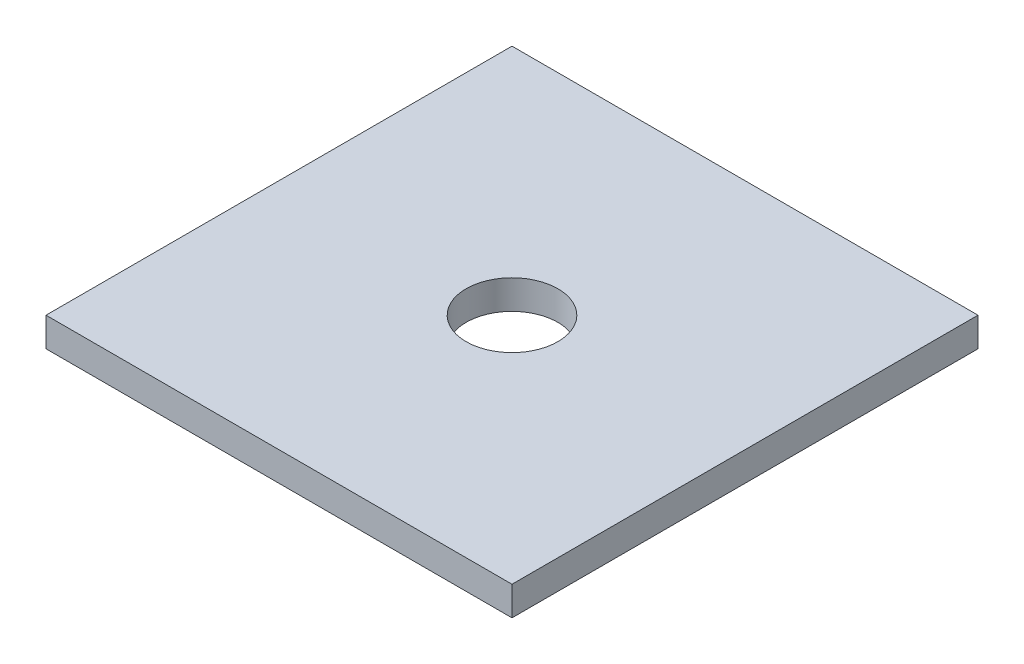
SolidWorks part; units mm, degrees
ref_plane "Front Plane" through (0, 0, 0) normal (0, 0, 1) x (1, 0, 0)
ref_plane "Top Plane" through (0, 0, 0) normal (0, 1, 0) x (1, 0, 0)
ref_plane "Right Plane" through (0, 0, 0) normal (1, 0, 0) x (0, 0, -1)
sketch "Sketch1" plane through (0, 0, 0) normal (0, 1, 0) x (1, 0, 0)
  line L1 (-50.8, 50.8) -> (50.8, 50.8)
  line L2 (-50.8, 50.8) -> (-50.8, -50.8)
  line L3 (-50.8, -50.8) -> (50.8, -50.8)
  line L4 (50.8, 50.8) -> (50.8, -50.8)
  line L5 (-50.8, 50.8) -> (50.8, -50.8) construction
  line L6 (-50.8, -50.8) -> (50.8, 50.8) construction
  circle A0 centre (0, 0) radius 10
  point P0 (0, 0)
  dimension "D3" = 20
  dimension "D1" = 101.6
  dimension "D2" = 101.6
extrude "Boss-Extrude1" add sketch "Sketch1" along normal blind 6.35
